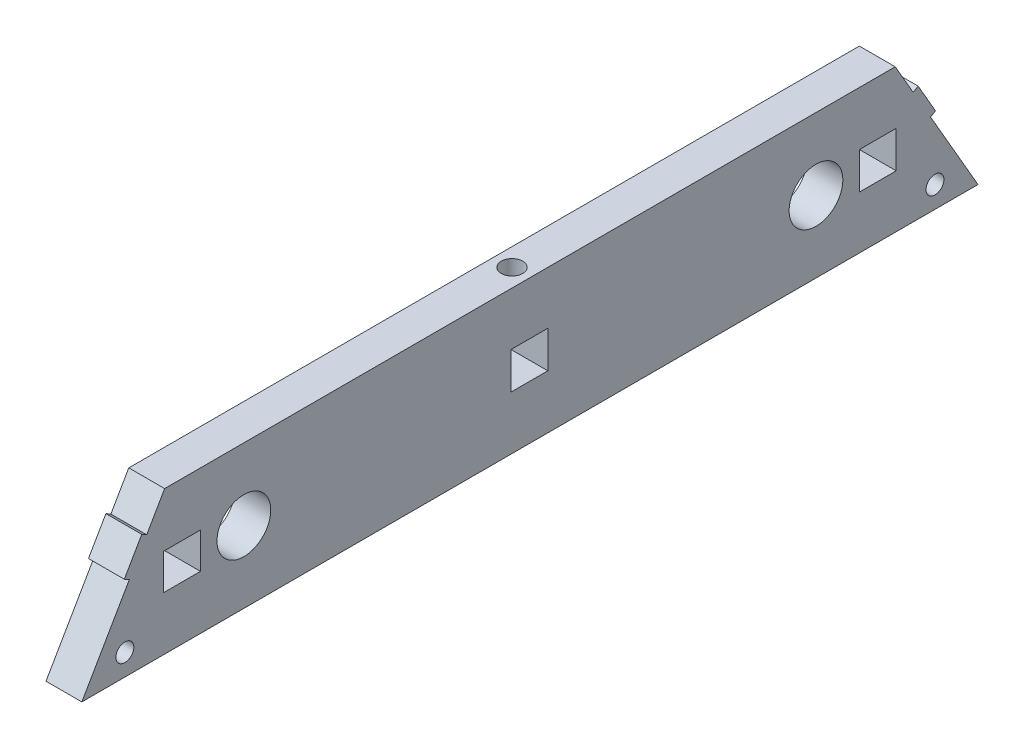
SolidWorks part; units mm, degrees
material "6061-T6 (SS)"
ref_plane "Front Plane" through (0, 0, 0) normal (0, 0, 1) x (1, 0, 0)
ref_plane "Top Plane" through (0, 0, 0) normal (0, 1, 0) x (1, 0, 0)
ref_plane "Right Plane" through (0, 0, 0) normal (1, 0, 0) x (0, 0, -1)
sketch "Sketch1" plane through (0, 0, 0) normal (1, 0, 0) x (0, 0, -1)
  line L0 (0, 0) -> (-14.6647, 25.4)
  line L1 (0, 0) -> (-158.75, 0)
  line L2 (-79.375, 25.4) -> (-79.375, 0.0032) construction
  line L3 (-14.6647, 25.4) -> (-144.0853, 25.4)
  line L4 (-21.0147, 9.3472) -> (-14.4869, 9.3472)
  line L5 (-158.75, 0) -> (-144.0853, 25.4)
  line L6 (-21.0147, 9.3472) -> (-21.0147, 15.875)
  line L7 (-21.0147, 15.875) -> (-14.4869, 15.875)
  line L8 (-14.4869, 9.3472) -> (-14.4869, 15.875)
  line L9 (-144.2631, 9.5262) -> (-144.2631, 15.875)
  line L10 (-137.7353, 15.875) -> (-144.2631, 15.875)
  line L11 (-137.7353, 9.5262) -> (-137.7353, 15.875)
  line L12 (-137.7353, 9.5262) -> (-144.2631, 9.5262)
  line L14 (-76.2, 16.0528) -> (-82.7278, 16.0528)
  line L15 (-76.2, 16.0528) -> (-76.2, 9.525)
  line L16 (-76.2, 9.525) -> (-82.7278, 9.525)
  line L17 (-82.7278, 16.0528) -> (-82.7278, 9.525)
  circle A0 centre (-130.048, 12.7) radius 4.7625
  circle A1 centre (-28.702, 12.7) radius 4.7625
  dimension "D3" = 9.525
  dimension "D5" = 9.525
  dimension "D9" = 60
  dimension "D12" = 6.5278
  dimension "D2" = 28.702
  dimension "D4" = 12.7
  dimension "D6" = 28.702
  dimension "D7" = 25.4
  dimension "D8" = 12.7
  dimension "D10" = 60
  dimension "D11" = 129.4206
  dimension "D13" = 6.5278
  dimension "D14" = 9.525
  dimension "D15" = 6.35
  dimension "D16" = 6.35
  dimension "D17" = 76.2
  dimension "D18" = 9.525
  dimension "D19" = 6.5278
  dimension "D20" = 6.5278
  dimension "D21" = 6.5278
  dimension "D22" = 6.3488
extrude "Boss-Extrude1" add sketch "Sketch1" along normal blind 6.35
hole_wizard "#6 Clearance Hole1" positions "Sketch6" profile "Sketch5" hole size "#6" standard "ANSI Inch"
sketch "Sketch6" plane through (0, 25.4, 0) normal (0, 1, 0) x (1, 0, 0)
  line L0 (6.35, 0) -> (0, 0) construction
  line L1 (0, -14.6647) -> (0, -144.0853) construction
  point P39 (3.175, -79.375)
  dimension "D1" = 79.375
  dimension "D2" = 3.175
sketch "Sketch5" plane through (3.175, 25.4, 79.375) normal (1, 0, 0) x (0, 0, 1)
  line L0 (0, 0) -> (0, 13.8408)
  line L1 (0, 13.8408) -> (1.8986, 12.7)
  line L2 (1.8986, 12.7) -> (1.8986, 0)
  line L5 (1.8986, 0) -> (0, 0)
  line L10 (0, 13.8408) -> (-1.8987, 12.7) construction
  line L11 (0, -6.35) -> (0, 107.95) construction
  dimension "Hole Dia." = 3.7973
  dimension "Hole Depth" = 12.7
  dimension "Drill Angle" = 118
sketch "Sketch7" plane through (0, 0, 0) normal (0, 0.5, -0.866) x (-1, 0, 0)
  line L0 (-6.35, 0) -> (-6.35, 29.3294) construction
  line L1 (-6.35, 22.9794) -> (0, 22.9794)
  line L2 (-6.35, 22.9794) -> (-6.35, 16.8072)
  line L3 (-6.35, 16.8072) -> (0, 16.8072)
  line L4 (0, 22.9794) -> (0, 16.8072)
  line L5 (0, 0) -> (0, 29.3294) construction
  line L6 (-6.35, 29.3294) -> (0, 29.3294) construction
  dimension "D1" = 6.1722
  dimension "D2" = 6.35
extrude "Boss-Extrude2" add sketch "Sketch7" along normal blind 1.016
sketch "Sketch8" plane through (0, 68.7408, 119.0625) normal (0, 0.5, 0.866) x (1, 0, 0)
  line L0 (0, -50.0456) -> (0, -79.375) construction
  line L1 (6.35, -50.0456) -> (6.35, -79.375) construction
  line L2 (0, -56.3956) -> (6.35, -56.3956)
  line L3 (0, -56.3956) -> (0, -62.5678)
  line L4 (0, -62.5678) -> (6.35, -62.5678)
  line L5 (6.35, -56.3956) -> (6.35, -62.5678)
  line L6 (6.35, -50.0456) -> (0, -50.0456) construction
  dimension "D1" = 6.1722
  dimension "D2" = 6.35
extrude "Boss-Extrude3" add sketch "Sketch8" along normal blind 1.016
sketch "Sketch9" plane through (6.35, 0, 0) normal (1, 0, 0) x (0, 0, -1)
  line L0 (-14.6647, 25.4) -> (-144.0853, 25.4) construction
  circle A0 centre (-151.13, 3.81) radius 1.5875
  circle A1 centre (-7.62, 3.81) radius 1.5875
  dimension "D1" = 3.175
  dimension "D4" = 3.175
  dimension "D2" = 21.59
  dimension "D3" = 7.62
  dimension "D5" = 21.59
  dimension "D6" = 7.62
extrude "Cut-Extrude1" cut sketch "Sketch9" against normal through all
sketch "Sketch11" plane through (0, 0, 0) normal (-1, 0, 0) x (0, 0, 1)
  line L0 (31.75, 2.1399) -> (34.1313, 3.5147)
  line L1 (14.6647, 25.4) -> (144.0853, 25.4) construction
  line L2 (19.05, 23.3871) -> (16.6687, 22.0123)
  line L3 (16.6687, 22.0123) -> (16.6687, 19.2627)
  line L4 (16.6687, 19.2627) -> (19.05, 17.8879)
  line L5 (19.05, 17.8879) -> (21.4312, 19.2627)
  line L6 (21.4312, 19.2627) -> (21.4312, 22.0123)
  line L7 (21.4312, 22.0123) -> (19.05, 23.3871)
  line L8 (0, -3.4925) -> (0, 3.4925) construction
  line L9 (25.4, 17.8879) -> (27.7812, 19.2627)
  line L10 (27.7812, 19.2627) -> (27.7812, 22.0123)
  line L11 (27.7812, 22.0123) -> (25.4, 23.3871)
  line L12 (25.4, 23.3871) -> (23.0187, 22.0123)
  line L13 (23.0187, 22.0123) -> (23.0187, 19.2627)
  line L14 (23.0187, 19.2627) -> (25.4, 17.8879)
  line L15 (31.75, 17.8879) -> (34.1312, 19.2627)
  line L16 (34.1312, 19.2627) -> (34.1312, 22.0123)
  line L17 (34.1312, 22.0123) -> (31.75, 23.3871)
  line L18 (31.75, 23.3871) -> (29.3687, 22.0123)
  line L19 (29.3687, 22.0123) -> (29.3687, 19.2627)
  line L20 (29.3687, 19.2627) -> (31.75, 17.8879)
  line L21 (38.1, 17.8879) -> (40.4812, 19.2627)
  line L22 (40.4812, 19.2627) -> (40.4812, 22.0123)
  line L23 (40.4812, 22.0123) -> (38.1, 23.3871)
  line L24 (38.1, 23.3871) -> (35.7187, 22.0123)
  line L25 (35.7187, 22.0123) -> (35.7187, 19.2627)
  line L26 (35.7187, 19.2627) -> (38.1, 17.8879)
  line L27 (44.45, 17.8879) -> (46.8312, 19.2627)
  line L28 (46.8312, 19.2627) -> (46.8312, 22.0123)
  line L29 (46.8312, 22.0123) -> (44.45, 23.3871)
  line L30 (44.45, 23.3871) -> (42.0688, 22.0123)
  line L31 (42.0688, 22.0123) -> (42.0688, 19.2627)
  line L32 (42.0688, 19.2627) -> (44.45, 17.8879)
  line L33 (50.8, 17.8879) -> (53.1812, 19.2627)
  line L34 (53.1812, 19.2627) -> (53.1812, 22.0123)
  line L35 (53.1812, 22.0123) -> (50.8, 23.3871)
  line L36 (50.8, 23.3871) -> (48.4187, 22.0123)
  line L37 (48.4187, 22.0123) -> (48.4187, 19.2627)
  line L38 (48.4187, 19.2627) -> (50.8, 17.8879)
  line L39 (57.15, 17.8879) -> (59.5312, 19.2627)
  line L40 (59.5312, 19.2627) -> (59.5312, 22.0123)
  line L41 (59.5312, 22.0123) -> (57.15, 23.3871)
  line L42 (57.15, 23.3871) -> (54.7687, 22.0123)
  line L43 (54.7687, 22.0123) -> (54.7687, 19.2627)
  line L44 (54.7687, 19.2627) -> (57.15, 17.8879)
  line L45 (63.5, 17.8879) -> (65.8812, 19.2627)
  line L46 (65.8812, 19.2627) -> (65.8812, 22.0123)
  line L47 (65.8812, 22.0123) -> (63.5, 23.3871)
  line L48 (63.5, 23.3871) -> (61.1187, 22.0123)
  line L49 (61.1187, 22.0123) -> (61.1187, 19.2627)
  line L50 (61.1187, 19.2627) -> (63.5, 17.8879)
  line L51 (69.85, 17.8879) -> (72.2313, 19.2627)
  line L52 (72.2313, 19.2627) -> (72.2313, 22.0123)
  line L53 (72.2313, 22.0123) -> (69.85, 23.3871)
  line L54 (69.85, 23.3871) -> (67.4688, 22.0123)
  line L55 (67.4688, 22.0123) -> (67.4688, 19.2627)
  line L56 (67.4688, 19.2627) -> (69.85, 17.8879)
  line L57 (76.2, 17.8879) -> (78.5812, 19.2627)
  line L58 (78.5812, 19.2627) -> (78.5812, 22.0123)
  line L59 (78.5812, 22.0123) -> (76.2, 23.3871)
  line L60 (76.2, 23.3871) -> (73.8188, 22.0123)
  line L61 (73.8188, 22.0123) -> (73.8188, 19.2627)
  line L62 (73.8188, 19.2627) -> (76.2, 17.8879)
  line L63 (82.55, 17.8879) -> (84.9313, 19.2627)
  line L64 (84.9313, 19.2627) -> (84.9313, 22.0123)
  line L65 (84.9313, 22.0123) -> (82.55, 23.3871)
  line L66 (82.55, 23.3871) -> (80.1688, 22.0123)
  line L67 (80.1688, 22.0123) -> (80.1688, 19.2627)
  line L68 (80.1688, 19.2627) -> (82.55, 17.8879)
  line L69 (88.9, 17.8879) -> (91.2812, 19.2627)
  line L70 (91.2812, 19.2627) -> (91.2812, 22.0123)
  line L71 (91.2812, 22.0123) -> (88.9, 23.3871)
  line L72 (88.9, 23.3871) -> (86.5187, 22.0123)
  line L73 (86.5187, 22.0123) -> (86.5187, 19.2627)
  line L74 (86.5187, 19.2627) -> (88.9, 17.8879)
  line L75 (95.25, 17.8879) -> (97.6312, 19.2627)
  line L76 (97.6312, 19.2627) -> (97.6312, 22.0123)
  line L77 (97.6312, 22.0123) -> (95.25, 23.3871)
  line L78 (95.25, 23.3871) -> (92.8687, 22.0123)
  line L79 (92.8687, 22.0123) -> (92.8687, 19.2627)
  line L80 (92.8687, 19.2627) -> (95.25, 17.8879)
  line L81 (101.6, 17.8879) -> (103.9813, 19.2627)
  line L82 (103.9813, 19.2627) -> (103.9813, 22.0123)
  line L83 (103.9813, 22.0123) -> (101.6, 23.3871)
  line L84 (101.6, 23.3871) -> (99.2188, 22.0123)
  line L85 (99.2188, 22.0123) -> (99.2188, 19.2627)
  line L86 (99.2188, 19.2627) -> (101.6, 17.8879)
  line L87 (107.95, 17.8879) -> (110.3312, 19.2627)
  line L88 (110.3312, 19.2627) -> (110.3312, 22.0123)
  line L89 (110.3312, 22.0123) -> (107.95, 23.3871)
  line L90 (107.95, 23.3871) -> (105.5687, 22.0123)
  line L91 (105.5687, 22.0123) -> (105.5687, 19.2627)
  line L92 (105.5687, 19.2627) -> (107.95, 17.8879)
  line L93 (114.3, 17.8879) -> (116.6813, 19.2627)
  line L94 (116.6813, 19.2627) -> (116.6813, 22.0123)
  line L95 (116.6813, 22.0123) -> (114.3, 23.3871)
  line L96 (114.3, 23.3871) -> (111.9188, 22.0123)
  line L97 (111.9188, 22.0123) -> (111.9188, 19.2627)
  line L98 (111.9188, 19.2627) -> (114.3, 17.8879)
  line L99 (120.65, 17.8879) -> (123.0312, 19.2627)
  line L100 (123.0312, 19.2627) -> (123.0312, 22.0123)
  line L101 (123.0312, 22.0123) -> (120.65, 23.3871)
  line L102 (120.65, 23.3871) -> (118.2687, 22.0123)
  line L103 (118.2687, 22.0123) -> (118.2687, 19.2627)
  line L104 (118.2687, 19.2627) -> (120.65, 17.8879)
  line L105 (127, 17.8879) -> (129.3812, 19.2627)
  line L106 (129.3812, 19.2627) -> (129.3812, 22.0123)
  line L107 (129.3812, 22.0123) -> (127, 23.3871)
  line L108 (127, 23.3871) -> (124.6187, 22.0123)
  line L109 (124.6187, 22.0123) -> (124.6187, 19.2627)
  line L110 (124.6187, 19.2627) -> (127, 17.8879)
  line L111 (133.35, 17.8879) -> (135.7312, 19.2627)
  line L112 (135.7312, 19.2627) -> (135.7312, 22.0123)
  line L113 (135.7312, 22.0123) -> (133.35, 23.3871)
  line L114 (133.35, 23.3871) -> (130.9688, 22.0123)
  line L115 (130.9688, 22.0123) -> (130.9688, 19.2627)
  line L116 (130.9688, 19.2627) -> (133.35, 17.8879)
  line L117 (139.7, 17.8879) -> (142.0812, 19.2627)
  line L118 (142.0812, 19.2627) -> (142.0812, 22.0123)
  line L119 (142.0812, 22.0123) -> (139.7, 23.3871)
  line L120 (139.7, 23.3871) -> (137.3187, 22.0123)
  line L121 (137.3187, 22.0123) -> (137.3187, 19.2627)
  line L122 (137.3187, 19.2627) -> (139.7, 17.8879)
  line L123 (38.1, 10.0139) -> (40.4813, 11.3887)
  line L124 (40.4813, 11.3887) -> (40.4813, 14.1383)
  line L125 (40.4813, 14.1383) -> (38.1, 15.5131)
  line L126 (38.1, 15.5131) -> (35.7188, 14.1383)
  line L127 (35.7188, 14.1383) -> (35.7188, 11.3887)
  line L128 (35.7188, 11.3887) -> (38.1, 10.0139)
  line L129 (44.45, 10.0139) -> (46.8313, 11.3887)
  line L130 (46.8313, 11.3887) -> (46.8313, 14.1383)
  line L131 (46.8313, 14.1383) -> (44.45, 15.5131)
  line L132 (44.45, 15.5131) -> (42.0688, 14.1383)
  line L133 (42.0688, 14.1383) -> (42.0688, 11.3887)
  line L134 (42.0688, 11.3887) -> (44.45, 10.0139)
  line L135 (50.8, 10.0139) -> (53.1813, 11.3887)
  line L136 (53.1813, 11.3887) -> (53.1813, 14.1383)
  line L137 (53.1813, 14.1383) -> (50.8, 15.5131)
  line L138 (50.8, 15.5131) -> (48.4188, 14.1383)
  line L139 (48.4188, 14.1383) -> (48.4188, 11.3887)
  line L140 (48.4188, 11.3887) -> (50.8, 10.0139)
  line L141 (57.15, 10.0139) -> (59.5313, 11.3887)
  line L142 (59.5313, 11.3887) -> (59.5313, 14.1383)
  line L143 (59.5313, 14.1383) -> (57.15, 15.5131)
  line L144 (57.15, 15.5131) -> (54.7688, 14.1383)
  line L145 (54.7688, 14.1383) -> (54.7688, 11.3887)
  line L146 (54.7688, 11.3887) -> (57.15, 10.0139)
  line L147 (63.5, 10.0139) -> (65.8813, 11.3887)
  line L148 (65.8813, 11.3887) -> (65.8813, 14.1383)
  line L149 (65.8813, 14.1383) -> (63.5, 15.5131)
  line L150 (63.5, 15.5131) -> (61.1188, 14.1383)
  line L151 (61.1188, 14.1383) -> (61.1188, 11.3887)
  line L152 (61.1188, 11.3887) -> (63.5, 10.0139)
  line L153 (69.85, 10.0139) -> (72.2313, 11.3887)
  line L154 (72.2313, 11.3887) -> (72.2313, 14.1383)
  line L155 (72.2313, 14.1383) -> (69.85, 15.5131)
  line L156 (69.85, 15.5131) -> (67.4688, 14.1383)
  line L157 (67.4688, 14.1383) -> (67.4688, 11.3887)
  line L158 (67.4688, 11.3887) -> (69.85, 10.0139)
  line L159 (38.1, 2.1399) -> (40.4813, 3.5147)
  line L160 (40.4813, 3.5147) -> (40.4813, 6.2643)
  line L161 (40.4813, 6.2643) -> (38.1, 7.6391)
  line L162 (38.1, 7.6391) -> (35.7188, 6.2643)
  line L163 (35.7188, 6.2643) -> (35.7188, 3.5147)
  line L164 (35.7188, 3.5147) -> (38.1, 2.1399)
  line L165 (44.45, 2.1399) -> (46.8313, 3.5147)
  line L166 (46.8313, 3.5147) -> (46.8313, 6.2643)
  line L167 (46.8313, 6.2643) -> (44.45, 7.6391)
  line L168 (44.45, 7.6391) -> (42.0688, 6.2643)
  line L169 (42.0688, 6.2643) -> (42.0688, 3.5147)
  line L170 (42.0688, 3.5147) -> (44.45, 2.1399)
  line L171 (50.8, 2.1399) -> (53.1813, 3.5147)
  line L172 (53.1813, 3.5147) -> (53.1813, 6.2643)
  line L173 (53.1813, 6.2643) -> (50.8, 7.6391)
  line L174 (50.8, 7.6391) -> (48.4188, 6.2643)
  line L175 (48.4188, 6.2643) -> (48.4188, 3.5147)
  line L176 (48.4188, 3.5147) -> (50.8, 2.1399)
  line L177 (57.15, 2.1399) -> (59.5313, 3.5147)
  line L178 (59.5313, 3.5147) -> (59.5313, 6.2643)
  line L179 (59.5313, 6.2643) -> (57.15, 7.6391)
  line L180 (57.15, 7.6391) -> (54.7688, 6.2643)
  line L181 (54.7688, 6.2643) -> (54.7688, 3.5147)
  line L182 (54.7688, 3.5147) -> (57.15, 2.1399)
  line L183 (63.5, 2.1399) -> (65.8813, 3.5147)
  line L184 (65.8813, 3.5147) -> (65.8813, 6.2643)
  line L185 (65.8813, 6.2643) -> (63.5, 7.6391)
  line L186 (63.5, 7.6391) -> (61.1188, 6.2643)
  line L187 (61.1188, 6.2643) -> (61.1188, 3.5147)
  line L188 (61.1188, 3.5147) -> (63.5, 2.1399)
  line L189 (69.85, 2.1399) -> (72.2313, 3.5147)
  line L190 (72.2313, 3.5147) -> (72.2313, 6.2643)
  line L191 (72.2313, 6.2643) -> (69.85, 7.6391)
  line L192 (69.85, 7.6391) -> (67.4688, 6.2643)
  line L193 (67.4688, 6.2643) -> (67.4688, 3.5147)
  line L194 (67.4688, 3.5147) -> (69.85, 2.1399)
  line L195 (34.1313, 3.5147) -> (34.1313, 6.2643)
  line L196 (34.1313, 6.2643) -> (31.75, 7.6391)
  line L197 (31.75, 7.6391) -> (29.3688, 6.2643)
  line L198 (29.3688, 6.2643) -> (29.3688, 3.5147)
  line L199 (29.3688, 3.5147) -> (31.75, 2.1399)
  line L200 (25.4, 2.1399) -> (27.7813, 3.5147)
  line L201 (27.7813, 3.5147) -> (27.7813, 6.2643)
  line L202 (27.7813, 6.2643) -> (25.4, 7.6391)
  line L203 (25.4, 7.6391) -> (23.0188, 6.2643)
  line L204 (23.0188, 6.2643) -> (23.0188, 3.5147)
  line L205 (23.0188, 3.5147) -> (25.4, 2.1399)
  line L206 (19.05, 2.1399) -> (21.4313, 3.5147)
  line L207 (21.4313, 3.5147) -> (21.4313, 6.2643)
  line L208 (21.4313, 6.2643) -> (19.05, 7.6391)
  line L209 (19.05, 7.6391) -> (16.6688, 6.2643)
  line L210 (16.6688, 6.2643) -> (16.6688, 3.5147)
  line L211 (16.6688, 3.5147) -> (19.05, 2.1399)
  line L212 (12.7, 2.1399) -> (15.0813, 3.5147)
  line L213 (15.0813, 3.5147) -> (15.0813, 6.2643)
  line L214 (15.0813, 6.2643) -> (12.7, 7.6391)
  line L215 (12.7, 7.6391) -> (10.3188, 6.2643)
  line L216 (10.3188, 6.2643) -> (10.3188, 3.5147)
  line L217 (10.3188, 3.5147) -> (12.7, 2.1399)
  line L218 (76.2, 2.1399) -> (78.5813, 3.5147)
  line L219 (78.5813, 3.5147) -> (78.5813, 6.2643)
  line L220 (78.5813, 6.2643) -> (76.2, 7.6391)
  line L221 (76.2, 7.6391) -> (73.8188, 6.2643)
  line L222 (73.8188, 6.2643) -> (73.8188, 3.5147)
  line L223 (73.8188, 3.5147) -> (76.2, 2.1399)
  line L224 (82.55, 2.1399) -> (84.9313, 3.5147)
  line L225 (84.9313, 3.5147) -> (84.9313, 6.2643)
  line L226 (84.9313, 6.2643) -> (82.55, 7.6391)
  line L227 (82.55, 7.6391) -> (80.1688, 6.2643)
  line L228 (80.1688, 6.2643) -> (80.1688, 3.5147)
  line L229 (80.1688, 3.5147) -> (82.55, 2.1399)
  line L230 (88.9, 2.1399) -> (91.2813, 3.5147)
  line L231 (91.2813, 3.5147) -> (91.2813, 6.2643)
  line L232 (91.2813, 6.2643) -> (88.9, 7.6391)
  line L233 (88.9, 7.6391) -> (86.5188, 6.2643)
  line L234 (86.5188, 6.2643) -> (86.5188, 3.5147)
  line L235 (86.5188, 3.5147) -> (88.9, 2.1399)
  line L236 (95.25, 2.1399) -> (97.6313, 3.5147)
  line L237 (97.6313, 3.5147) -> (97.6313, 6.2643)
  line L238 (97.6313, 6.2643) -> (95.25, 7.6391)
  line L239 (95.25, 7.6391) -> (92.8688, 6.2643)
  line L240 (92.8688, 6.2643) -> (92.8688, 3.5147)
  line L241 (92.8688, 3.5147) -> (95.25, 2.1399)
  line L242 (101.6, 2.1399) -> (103.9813, 3.5147)
  line L243 (103.9813, 3.5147) -> (103.9813, 6.2643)
  line L244 (103.9813, 6.2643) -> (101.6, 7.6391)
  line L245 (101.6, 7.6391) -> (99.2188, 6.2643)
  line L246 (99.2188, 6.2643) -> (99.2188, 3.5147)
  line L247 (99.2188, 3.5147) -> (101.6, 2.1399)
  line L248 (107.95, 2.1399) -> (110.3313, 3.5147)
  line L249 (110.3313, 3.5147) -> (110.3313, 6.2643)
  line L250 (110.3313, 6.2643) -> (107.95, 7.6391)
  line L251 (107.95, 7.6391) -> (105.5688, 6.2643)
  line L252 (105.5688, 6.2643) -> (105.5688, 3.5147)
  line L253 (105.5688, 3.5147) -> (107.95, 2.1399)
  line L254 (114.3, 2.1399) -> (116.6813, 3.5147)
  line L255 (116.6813, 3.5147) -> (116.6813, 6.2643)
  line L256 (116.6813, 6.2643) -> (114.3, 7.6391)
  line L257 (114.3, 7.6391) -> (111.9188, 6.2643)
  line L258 (111.9188, 6.2643) -> (111.9188, 3.5147)
  line L259 (111.9188, 3.5147) -> (114.3, 2.1399)
  line L260 (120.65, 2.1399) -> (123.0313, 3.5147)
  line L261 (123.0313, 3.5147) -> (123.0313, 6.2643)
  line L262 (123.0313, 6.2643) -> (120.65, 7.6391)
  line L263 (120.65, 7.6391) -> (118.2688, 6.2643)
  line L264 (118.2688, 6.2643) -> (118.2688, 3.5147)
  line L265 (118.2688, 3.5147) -> (120.65, 2.1399)
  line L266 (127, 2.1399) -> (129.3813, 3.5147)
  line L267 (129.3813, 3.5147) -> (129.3813, 6.2643)
  line L268 (129.3813, 6.2643) -> (127, 7.6391)
  line L269 (127, 7.6391) -> (124.6188, 6.2643)
  line L270 (124.6188, 6.2643) -> (124.6188, 3.5147)
  line L271 (124.6188, 3.5147) -> (127, 2.1399)
  line L272 (133.35, 2.1399) -> (135.7313, 3.5147)
  line L273 (135.7313, 3.5147) -> (135.7313, 6.2643)
  line L274 (135.7313, 6.2643) -> (133.35, 7.6391)
  line L275 (133.35, 7.6391) -> (130.9688, 6.2643)
  line L276 (130.9688, 6.2643) -> (130.9688, 3.5147)
  line L277 (130.9688, 3.5147) -> (133.35, 2.1399)
  line L278 (139.7, 2.1399) -> (142.0813, 3.5147)
  line L279 (142.0813, 3.5147) -> (142.0813, 6.2643)
  line L280 (142.0813, 6.2643) -> (139.7, 7.6391)
  line L281 (139.7, 7.6391) -> (137.3188, 6.2643)
  line L282 (137.3188, 6.2643) -> (137.3188, 3.5147)
  line L283 (137.3188, 3.5147) -> (139.7, 2.1399)
  line L284 (146.05, 2.1399) -> (148.4313, 3.5147)
  line L285 (148.4313, 3.5147) -> (148.4313, 6.2643)
  line L286 (148.4313, 6.2643) -> (146.05, 7.6391)
  line L287 (146.05, 7.6391) -> (143.6688, 6.2643)
  line L288 (143.6688, 6.2643) -> (143.6688, 3.5147)
  line L289 (143.6688, 3.5147) -> (146.05, 2.1399)
  line L290 (88.9, 9.9504) -> (91.2813, 11.3252)
  line L291 (91.2813, 11.3252) -> (91.2813, 14.0748)
  line L292 (91.2813, 14.0748) -> (88.9, 15.4496)
  line L293 (88.9, 15.4496) -> (86.5188, 14.0748)
  line L294 (86.5188, 14.0748) -> (86.5188, 11.3252)
  line L295 (86.5188, 11.3252) -> (88.9, 9.9504)
  line L296 (95.25, 9.9504) -> (97.6313, 11.3252)
  line L297 (97.6313, 11.3252) -> (97.6313, 14.0748)
  line L298 (97.6313, 14.0748) -> (95.25, 15.4496)
  line L299 (95.25, 15.4496) -> (92.8688, 14.0748)
  line L300 (92.8688, 14.0748) -> (92.8688, 11.3252)
  line L301 (92.8688, 11.3252) -> (95.25, 9.9504)
  line L302 (101.6, 9.9504) -> (103.9813, 11.3252)
  line L303 (103.9813, 11.3252) -> (103.9813, 14.0748)
  line L304 (103.9813, 14.0748) -> (101.6, 15.4496)
  line L305 (101.6, 15.4496) -> (99.2188, 14.0748)
  line L306 (99.2188, 14.0748) -> (99.2188, 11.3252)
  line L307 (99.2188, 11.3252) -> (101.6, 9.9504)
  line L308 (107.95, 9.9504) -> (110.3313, 11.3252)
  line L309 (110.3313, 11.3252) -> (110.3313, 14.0748)
  line L310 (110.3313, 14.0748) -> (107.95, 15.4496)
  line L311 (107.95, 15.4496) -> (105.5688, 14.0748)
  line L312 (105.5688, 14.0748) -> (105.5688, 11.3252)
  line L313 (105.5688, 11.3252) -> (107.95, 9.9504)
  line L314 (114.3, 9.9504) -> (116.6813, 11.3252)
  line L315 (116.6813, 11.3252) -> (116.6813, 14.0748)
  line L316 (116.6813, 14.0748) -> (114.3, 15.4496)
  line L317 (114.3, 15.4496) -> (111.9188, 14.0748)
  line L318 (111.9188, 14.0748) -> (111.9188, 11.3252)
  line L319 (111.9188, 11.3252) -> (114.3, 9.9504)
  line L320 (120.65, 9.9504) -> (123.0313, 11.3252)
  line L321 (123.0313, 14.0748) -> (120.65, 15.4496)
  line L322 (120.65, 15.4496) -> (118.2688, 14.0748)
  line L323 (118.2688, 14.0748) -> (118.2688, 11.3252)
  line L324 (118.2688, 11.3252) -> (120.65, 9.9504)
  line L325 (123.0313, 11.3252) -> (123.0313, 14.0748)
  circle A0 centre (19.05, 20.6375) radius 2.3813 construction
  dimension "D1" = 4.7625
  dimension "D2" = 19.05
  dimension "D4" = 20
  dimension "D3" = 3
extrude "Cut-Extrude3" [suppressed] cut sketch "Sketch11" against normal through all
equation "\"D8@Sketch1\"=\"D4@Sketch1\""
